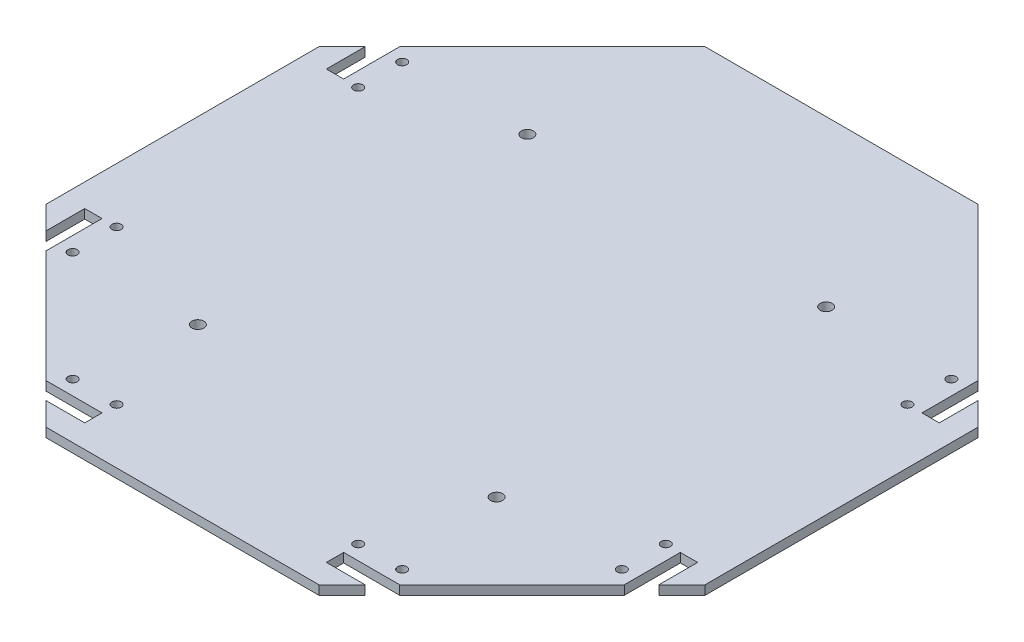
SolidWorks part; units mm, degrees
ref_plane "Front Plane" through (0, 0, 0) normal (0, 0, 1) x (1, 0, 0)
ref_plane "Top Plane" through (0, 0, 0) normal (0, 1, 0) x (1, 0, 0)
ref_plane "Right Plane" through (0, 0, 0) normal (1, 0, 0) x (0, 0, -1)
sketch "Sketch1" plane through (0, 0, 0) normal (0, 1, 0) x (1, 0, 0)
  line L1 (0, 139.7) -> (152.4, 139.7) construction
  line L2 (152.4, 139.7) -> (152.4, 0) construction
  line L4 (76.2, 139.7) -> (76.2, 0) construction
  line L8 (24.384, 0) -> (24.384, 12.7) construction
  line L9 (1.3179, 69.85) -> (152.4, 69.85) construction
  line L10 (0, 139.7) -> (0, 0) construction
  line L11 (0, 0) -> (152.4, 0) construction
  line L12 (24.384, 12.7) -> (0, 12.7) construction
  line L13 (128.016, 0) -> (128.016, 12.7) construction
  line L14 (128.016, 12.7) -> (152.4, 12.7) construction
  line L15 (128.016, 127) -> (152.4, 127) construction
  line L16 (128.016, 139.7) -> (128.016, 127) construction
  line L17 (24.384, 139.7) -> (24.384, 127) construction
  line L18 (24.384, 127) -> (0, 127) construction
  line L19 (76.2, -44.45) -> (76.2, 184.15) construction
  line L20 (-38.1, 69.85) -> (190.5, 69.85) construction
  line L21 (28.8554, 184.15) -> (123.5446, 184.15)
  line L22 (190.5, 22.5054) -> (190.5, 117.1946)
  line L23 (28.8554, -44.45) -> (123.5446, -44.45)
  line L24 (-38.1, 22.5054) -> (-38.1, 117.1946)
  line L29 (28.8554, 184.15) -> (-24.1, 131.1946)
  line L30 (123.5446, 184.15) -> (176.5, 131.1946)
  line L31 (-38.1, 22.5054) -> (-30.1, 14.5054)
  line L32 (190.5, 22.5054) -> (182.5, 14.5054)
  line L33 (-38.1, 69.85) -> (-24.1, 69.85) construction
  line L34 (-24.1, 27.94) -> (-24.1, 111.76) construction
  line L35 (-30.1, 125.1946) -> (-38.1, 117.1946)
  line L36 (-24.1, 111.76) -> (-30.1, 111.76)
  line L37 (-24.1, 111.76) -> (-24.1, 131.1946)
  line L39 (-30.1, 111.76) -> (-30.1, 125.1946)
  line L40 (-24.1, 8.5054) -> (14.8554, -30.45)
  line L41 (-24.1, 27.94) -> (-30.1, 27.94)
  line L42 (-24.1, 27.94) -> (-24.1, 8.5054)
  line L44 (-30.1, 27.94) -> (-30.1, 14.5054)
  line L45 (-4.6223, -10.9723) -> (157.0223, 150.6723) construction
  line L46 (34.29, -30.45) -> (118.11, -30.45) construction
  line L47 (76.2, -44.45) -> (76.2, -30.45) construction
  line L48 (34.29, -36.45) -> (20.8554, -36.45)
  line L49 (34.29, -30.45) -> (14.8554, -30.45)
  line L50 (34.29, -30.45) -> (34.29, -36.45)
  line L51 (118.11, -36.45) -> (131.5446, -36.45)
  line L52 (118.11, -30.45) -> (137.5446, -30.45)
  line L53 (118.11, -30.45) -> (118.11, -36.45)
  line L54 (176.5, 27.94) -> (176.5, 111.76) construction
  line L55 (190.5, 69.85) -> (176.5, 69.85) construction
  line L56 (182.5, 27.94) -> (182.5, 14.5054)
  line L57 (176.5, 27.94) -> (176.5, 8.5054)
  line L58 (176.5, 27.94) -> (182.5, 27.94)
  line L59 (182.5, 111.76) -> (182.5, 125.1946)
  line L60 (176.5, 111.76) -> (176.5, 131.1946)
  line L61 (176.5, 111.76) -> (182.5, 111.76)
  line L62 (20.8554, -36.45) -> (28.8554, -44.45)
  line L63 (131.5446, -36.45) -> (123.5446, -44.45)
  line L64 (176.5, 8.5054) -> (137.5446, -30.45)
  line L65 (182.5, 125.1946) -> (190.5, 117.1946)
  circle A0 centre (24.384, 12.7) radius 2.0828
  circle A1 centre (128.016, 12.7) radius 2.0828
  circle A2 centre (128.016, 127) radius 2.0828
  circle A3 centre (24.384, 127) radius 2.0828
  point P28 (76.2, 69.85)
  point P31 (76.2, 69.85)
  point P34 (76.2, 184.15)
  point P37 (190.5, 69.85)
  point P40 (76.2, -44.45)
  point P46 (-24.1, 69.85)
  point P55 (76.2, 69.85)
  dimension "D3" = 24.384
  dimension "D1" = 139.7
  dimension "D2" = 152.4
  dimension "D4" = 12.7
  dimension "D5" = 94.6892
  dimension "D6" = 228.6
extrude "Boss-Extrude1" add sketch "Sketch1" along normal blind 3.175
sketch "Sketch5" plane through (0, 3.175, 0) normal (0, 1, 0) x (1, 0, 0)
  line L0 (-38.1, 69.85) -> (-19.05, 69.85) construction
  line L1 (-38.1, 117.1946) -> (-38.1, 22.5054) construction
  line L2 (-19.05, 27.94) -> (-19.05, 111.76) construction
  line L3 (-19.05, 111.76) -> (-19.05, 127) construction
  line L4 (76.2, 184.15) -> (76.2, -44.45) construction
  line L5 (123.5446, 184.15) -> (28.8554, 184.15) construction
  line L6 (28.8554, -44.45) -> (123.5446, -44.45) construction
  line L7 (-19.05, 27.94) -> (-19.05, 12.7) construction
  line L8 (190.5, 69.85) -> (171.45, 69.85) construction
  line L9 (171.45, 111.76) -> (171.45, 127) construction
  line L10 (171.45, 27.94) -> (171.45, 111.76) construction
  line L11 (171.45, 27.94) -> (171.45, 12.7) construction
  line L12 (-4.6223, -10.9723) -> (157.0223, 150.6723) construction
  line L17 (34.29, -25.4) -> (19.05, -25.4) construction
  line L18 (118.11, -25.4) -> (133.35, -25.4) construction
  line L19 (34.29, -25.4) -> (118.11, -25.4) construction
  line L20 (76.2, -44.45) -> (76.2, -25.4) construction
  circle A0 centre (-19.05, 119.38) radius 1.524
  circle A1 centre (-19.05, 20.32) radius 1.524
  circle A2 centre (171.45, 20.32) radius 1.524
  circle A3 centre (171.45, 119.38) radius 1.524
  circle A6 centre (26.67, -25.4) radius 1.524
  circle A7 centre (125.73, -25.4) radius 1.524
  point P7 (-19.05, 69.85)
  dimension "D1" = 41.91
  dimension "D2" = 15.24
  dimension "D3" = 19.05
hole_wizard "M3 Clearance Hole1" positions "Sketch8" profile "Sketch9" hole size "M3" standard "ANSI Metric" end condition through all
sketch "Sketch8" plane through (0, 3.175, 0) normal (0, 1, 0) x (1, 0, 0)
  point P0 (-19.05, 127)
  point P3 (-19.05, 111.76)
  point P6 (-19.05, 27.94)
  point P9 (-19.05, 12.7)
  point P12 (171.45, 127)
  point P15 (171.45, 111.76)
  point P18 (171.45, 27.94)
  point P21 (171.45, 12.7)
  point P25 (133.35, -25.4)
  point P28 (118.11, -25.4)
  point P31 (34.29, -25.4)
  point P34 (19.05, -25.4)
sketch "Sketch9" plane through (-19.05, 3.175, -127) normal (1, 0, 0) x (0, 0, 1)
  line L0 (0, 0) -> (0, 3.175)
  line L1 (0, 3.175) -> (1.6, 3.175)
  line L2 (1.6, 3.175) -> (1.6, 0)
  line L5 (1.6, 0) -> (0, 0)
  line L11 (0, -6.35) -> (0, 107.95) construction
  dimension "Thru Hole Dia." = 3.2
  dimension "Thru Hole Depth" = 3.175
